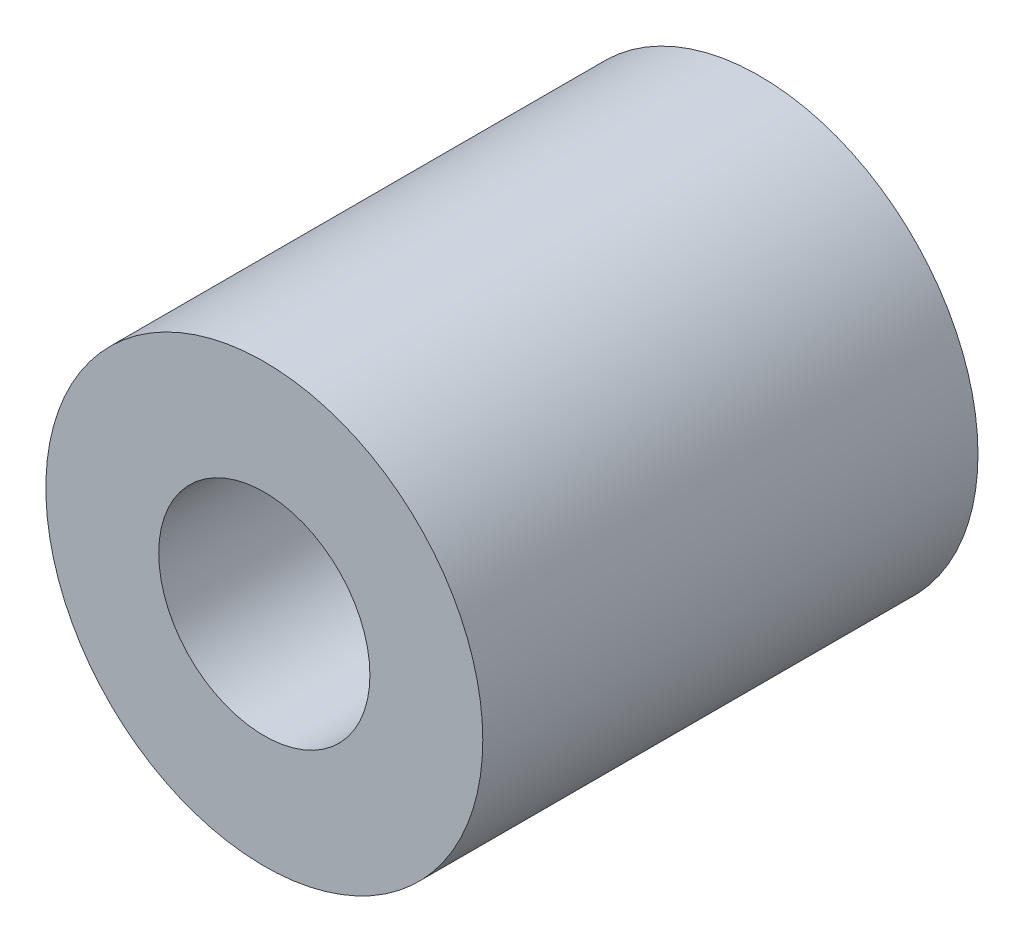
SolidWorks part; units mm, degrees
ref_plane "Front Plane" through (0, 0, 0) normal (0, 0, 1) x (1, 0, 0)
ref_plane "Top Plane" through (0, 0, 0) normal (0, 1, 0) x (1, 0, 0)
ref_plane "Right Plane" through (0, 0, 0) normal (1, 0, 0) x (0, 0, -1)
sketch "Sketch1" plane through (0, 0, 0) normal (0, 0, 1) x (1, 0, 0)
  circle A0 centre (0, 0) radius 15
  dimension "D1" = 30
extrude "Boss-Extrude1" add sketch "Sketch1" along normal blind 34
sketch "Sketch2" plane through (0, 0, 0) normal (1, 0, 0) x (0, 0, -1)
  line L0 (0, 0) -> (0, 3.175)
  line L1 (0, -15) -> (0, 15) construction
  line L2 (0, 3.175) -> (-17, 3.175)
  line L3 (-17, 3.175) -> (-17, 7.25)
  line L4 (-17, 7.25) -> (-34, 7.25)
  line L5 (-34, 15) -> (-34, -15) construction
  line L6 (-34, 7.25) -> (-34, 0)
  line L7 (-34, 0) -> (0, 0)
  point P5 (-17, 0)
  dimension "D1" = 3.175
  dimension "D2" = 7.25
revolve "Cut-Revolve1" cut sketch "Sketch2" angle 360 about L7
